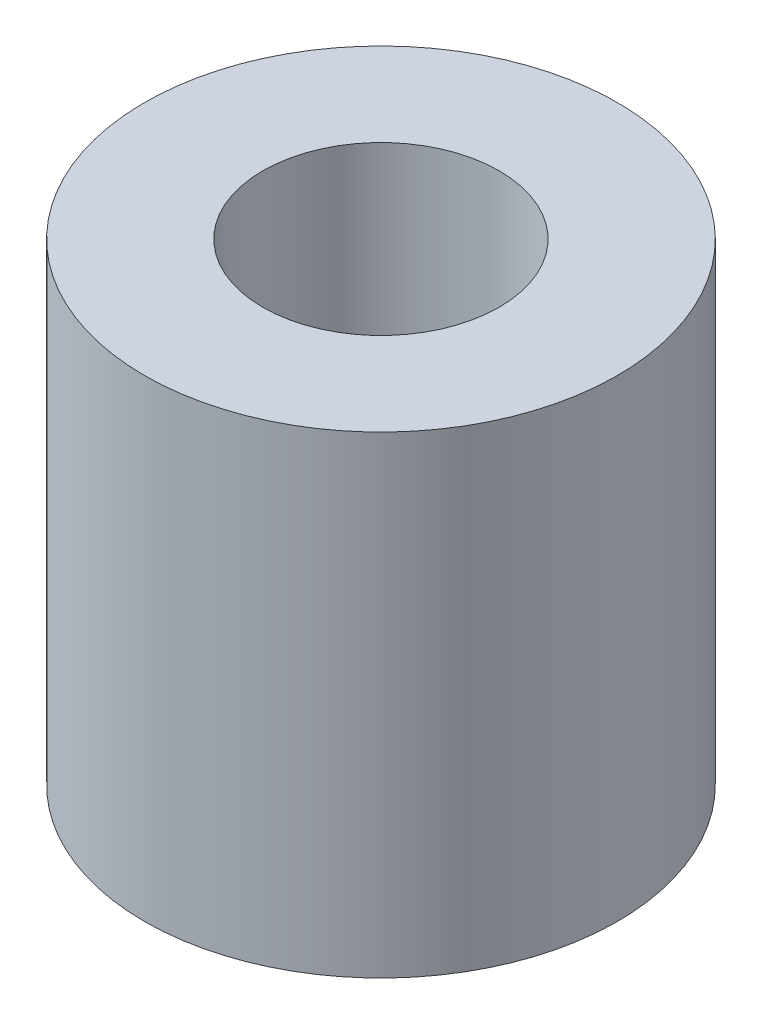
SolidWorks part; units mm, degrees
ref_plane "Front Plane" through (0, 0, 0) normal (0, 0, 1) x (1, 0, 0)
ref_plane "Top Plane" through (0, 0, 0) normal (0, 1, 0) x (1, 0, 0)
ref_plane "Right Plane" through (0, 0, 0) normal (1, 0, 0) x (0, 0, -1)
sketch "Sketch1" plane through (0, 0, 0) normal (0, 1, 0) x (1, 0, 0)
  circle A0 centre (0, 0) radius 0.5
  circle A1 centre (0, 0) radius 1
  dimension "D1" = 1
  dimension "D2" = 0.5
extrude "Boss-Extrude1" add sketch "Sketch1" along normal blind 2
